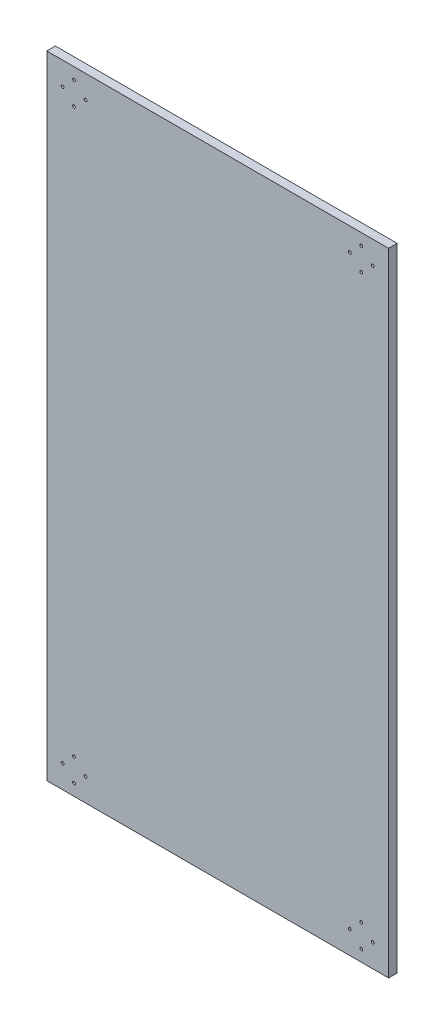
SolidWorks part; units mm, degrees
material "Balsa"
ref_plane "Front Plane" through (0, 0, 0) normal (0, 0, 1) x (1, 0, 0)
ref_plane "Top Plane" through (0, 0, 0) normal (0, 1, 0) x (1, 0, 0)
ref_plane "Right Plane" through (0, 0, 0) normal (1, 0, 0) x (0, 0, -1)
sketch "Sketch1" plane through (0, 0, 0) normal (0, 0, 1) x (1, 0, 0)
  line L1 (0, 0) -> (755.65, 0)
  line L2 (0, 0) -> (0, 1397)
  line L3 (0, 1397) -> (755.65, 1397)
  line L4 (755.65, 0) -> (755.65, 1397)
  dimension "D1" = 755.65
  dimension "D2" = 1397
extrude "Boss-Extrude1" add sketch "Sketch1" along normal blind 19.05
sketch "Sketch2" plane through (0, 0, 19.05) normal (0, 0, 1) x (1, 0, 0)
  line L1 (0, 1397) -> (0, 0) construction
  line L2 (755.65, 1397) -> (0, 1397) construction
  line L3 (0, 0) -> (755.65, 0) construction
  line L4 (0, 698.5) -> (755.65, 698.5) construction
  line L5 (755.65, 0) -> (755.65, 1397) construction
  line L6 (377.825, 1397) -> (377.825, 0) construction
  circle A4 centre (60.325, 76.2) radius 3.175
  circle A5 centre (60.325, 25.4) radius 3.175
  circle A6 centre (34.925, 50.8) radius 3.175
  circle A7 centre (85.725, 50.8) radius 3.175
  circle A8 centre (669.925, 50.8) radius 3.175
  circle A9 centre (720.725, 50.8) radius 3.175
  circle A10 centre (695.325, 25.4) radius 3.175
  circle A11 centre (695.325, 76.2) radius 3.175
  circle A12 centre (695.325, 1320.8) radius 3.175
  circle A13 centre (695.325, 1371.6) radius 3.175
  circle A14 centre (720.725, 1346.2) radius 3.175
  circle A15 centre (669.925, 1346.2) radius 3.175
  circle A16 centre (85.725, 1346.2) radius 3.175
  circle A17 centre (34.925, 1346.2) radius 3.175
  circle A18 centre (60.325, 1371.6) radius 3.175
  circle A19 centre (60.325, 1320.8) radius 3.175
  dimension "D2" = 6.35
  dimension "D4" = 6.35
  dimension "D5" = 6.35
  dimension "D6" = 25.4
  dimension "D3" = 6.35
  dimension "D13" = 25.4
  dimension "D14" = 25.4
  dimension "D15" = 25.4
  dimension "D16" = 34.925
  dimension "D17" = 25.4
extrude "Cut-Extrude1" cut sketch "Sketch2" against normal blind 25.4
